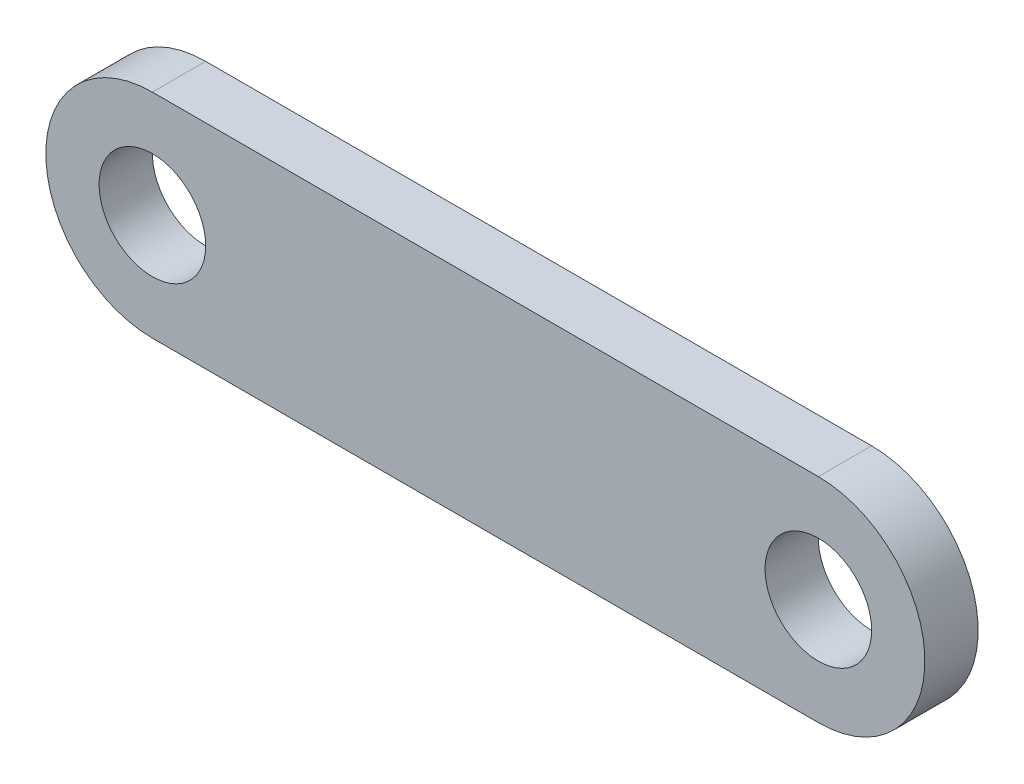
SolidWorks part; units mm, degrees
ref_plane "Front Plane" through (0, 0, 0) normal (0, 0, 1) x (1, 0, 0)
ref_plane "Top Plane" through (0, 0, 0) normal (0, 1, 0) x (1, 0, 0)
ref_plane "Right Plane" through (0, 0, 0) normal (1, 0, 0) x (0, 0, -1)
sketch "Sketch1" plane through (0, 0, 0) normal (0, 0, 1) x (1, 0, 0)
  line L0 (0, 0) -> (-62.5, 0) construction
  line L1 (0, -10) -> (-62.5, -10)
  line L2 (0, 10) -> (-62.5, 10)
  arc A0 (0, -10) -> (0, 10) centre (0, 0) ccw
  arc A1 (-62.5, 10) -> (-62.5, -10) centre (-62.5, 0) ccw
  circle A2 centre (-62.5, 0) radius 5
  circle A3 centre (0, 0) radius 5
  point P3 (-31.25, 0)
  dimension "D3" = 10
  dimension "D4" = 10
  dimension "D1" = 20
  dimension "D2" = 62.5
extrude "Boss-Extrude1" add sketch "Sketch1" along normal mid plane 5
